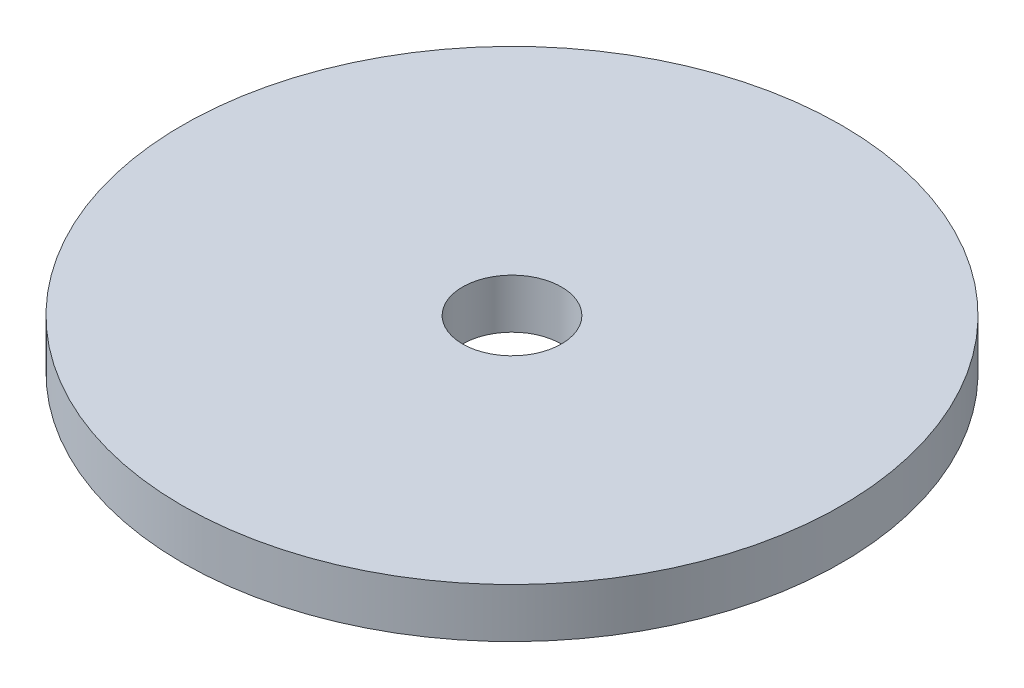
SolidWorks part; units mm, degrees
material "ASTM A36 Steel"
ref_plane "Front Plane" through (0, 0, 0) normal (0, 0, 1) x (1, 0, 0)
ref_plane "Top Plane" through (0, 0, 0) normal (0, 1, 0) x (1, 0, 0)
ref_plane "Right Plane" through (0, 0, 0) normal (1, 0, 0) x (0, 0, -1)
sketch "Sketch1" plane through (0, 0, 0) normal (0, 1, 0) x (1, 0, 0)
  circle A0 centre (0, 0) radius 6
  circle A1 centre (0, 0) radius 40
  dimension "D1" = 80
  dimension "D2" = 12
extrude "Boss-Extrude1" add sketch "Sketch1" along normal blind 6
